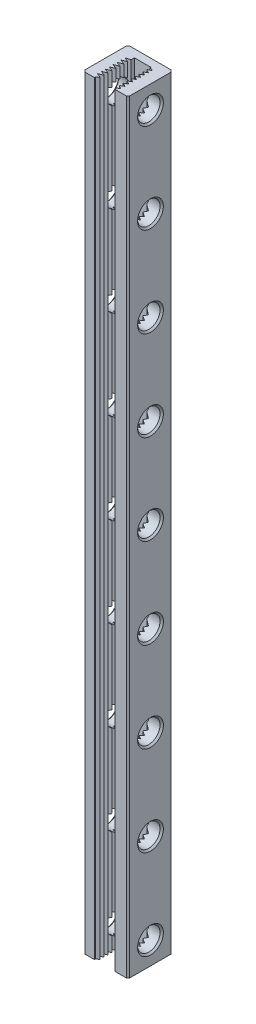
SolidWorks part; units mm, degrees
ref_plane "Front Plane" through (0, 0, 0) normal (0, 0, 1) x (1, 0, 0)
ref_plane "Top Plane" through (0, 0, 0) normal (0, 1, 0) x (1, 0, 0)
ref_plane "Right Plane" through (0, 0, 0) normal (1, 0, 0) x (0, 0, -1)
sketch "Sketch1" plane through (0, 0, 0) normal (0, 1, 0) x (1, 0, 0)
  line L1 (0, 0) -> (8, 0)
  line L2 (0, 0) -> (0, 8)
  line L3 (0, 8) -> (8, 8)
  line L4 (8, 0) -> (8, 8)
  dimension "D1" = 8
  dimension "D2" = 8
extrude "Boss-Extrude1" add sketch "Sketch1" along normal blind 300
sketch "Sketch2" plane through (0, 0, 0) normal (0, -1, 0) x (1, 0, 0)
  line L0 (5.652, 0) -> (2.0084, 0)
  line L1 (2.0084, 0) -> (2.0084, -0.2082)
  line L2 (2.0084, -0.2082) -> (2.54, -0.5151)
  line L3 (2.54, -0.5151) -> (1.6737, -0.8651)
  line L4 (1.6737, -0.8651) -> (2.54, -1.2151)
  line L5 (2.54, -1.2151) -> (1.6737, -1.5727)
  line L6 (1.6737, -1.5727) -> (2.54, -1.9151)
  line L7 (2.54, -1.9151) -> (1.6737, -2.2651)
  line L8 (1.6737, -2.2651) -> (2.54, -2.6151)
  line L9 (2.54, -2.6151) -> (1.6737, -2.9651)
  line L10 (1.6737, -2.9651) -> (2.54, -3.3151)
  line L11 (2.54, -3.3151) -> (1.6737, -3.6651)
  line L12 (1.6737, -3.6651) -> (2.54, -4.0151)
  line L13 (2.54, -4.0151) -> (1.6737, -4.3651)
  line L14 (1.6737, -4.3651) -> (2.54, -4.7151)
  line L15 (2.54, -4.7151) -> (1.6737, -5.0651)
  line L16 (1.6737, -5.0651) -> (2.54, -5.4151)
  line L17 (2.54, -5.4151) -> (1.6737, -5.7651)
  line L18 (1.6737, -5.7651) -> (2.54, -6.0264)
  line L19 (2.54, -6.0264) -> (2.54, -6.6)
  line L20 (2.54, -6.6) -> (5.46, -6.6)
  line L21 (5.46, -6.6) -> (5.46, -6.4988)
  line L22 (5.46, -6.4988) -> (6.1067, -6.2375)
  line L23 (6.1067, -6.2375) -> (5.46, -5.8875)
  line L24 (5.46, -5.8875) -> (6.1067, -5.5375)
  line L25 (6.1067, -5.5375) -> (5.46, -5.1875)
  line L26 (5.46, -5.1875) -> (6.1067, -4.8375)
  line L27 (6.1067, -4.8375) -> (5.46, -4.4875)
  line L28 (5.46, -4.4875) -> (6.1067, -4.1375)
  line L29 (6.1067, -4.1375) -> (5.46, -3.7875)
  line L30 (5.46, -3.7875) -> (6.1067, -3.4375)
  line L31 (6.1067, -3.4375) -> (5.46, -3.0875)
  line L32 (5.46, -3.0875) -> (6.1067, -2.7375)
  line L33 (6.1067, -2.7375) -> (5.46, -2.3875)
  line L34 (5.46, -2.3875) -> (6.1067, -2.0375)
  line L35 (6.1067, -2.0375) -> (5.46, -1.6875)
  line L36 (5.46, -1.6875) -> (6.1067, -1.3451)
  line L37 (6.1067, -1.3451) -> (5.46, -0.9875)
  line L38 (5.46, -0.9875) -> (6.1067, -0.6375)
  line L39 (6.1067, -0.6375) -> (5.652, -0.375)
  line L40 (5.652, -0.375) -> (5.652, 0)
  line L41 (0, -8) -> (0, 0) construction
  line L42 (8, -8) -> (0, -8) construction
  line L43 (0, 0) -> (8, 0) construction
  point P41 (0, 0)
  point P42 (0, 0)
  point P43 (0, 0)
  point P44 (0, 0)
  point P51 (0, 0)
  point P52 (0, 0)
  point P53 (4, -6.6)
  dimension "D1" = 2.92
  dimension "D2" = 0.8663
  dimension "D3" = 6.6
  dimension "D4" = 0.6467
  dimension "D5" = 4.433
  dimension "D6" = 4
extrude "Cut-Extrude1" cut sketch "Sketch2" against normal through all contours L0 L1 L2 L3 L4 L5 L6 L7 L8 L9 L10 L11 L12 L13 L14 L15 L16 L17 L18 L19 L20 L21 L22 L23 L24 L25 L26 L27 L28 L29 L30 L31 L32 L33 L34 L35 L36 L37 L38 L39 L40
sketch "Sketch3" plane through (8, 0, 0) normal (1, 0, 0) x (0, 0, -1)
  line L0 (0, 0) -> (8, 0) construction
  line L1 (8, 300) -> (8, 0) construction
  circle A0 centre (4, 4) radius 2
  dimension "D1" = 4
  dimension "D2" = 4
  dimension "D3" = 4
extrude "Cut-Extrude2" cut sketch "Sketch3" against normal through all
chamfer "Chamfer1" distance 0.3 angle 45 2 edges at (0, 4, -6) (8, 4, -6)
chamfer "Chamfer2" distance 0.3 angle 45 4 edges at (0, 150, -8) (0, 150, 0) (8, 150, -8) (8, 150, 0)
pattern_linear "LPattern1" count 19 spacing 16 along (0, 1, 0) of "Cut-Extrude2", "Chamfer1"
sketch "Sketch4" plane through (8, 0, 0) normal (1, 0, 0) x (0, 0, -1)
  line L0 (0.3, 300) -> (7.7, 300) construction
  line L1 (8, 300) -> (0, 300)
  line L2 (8, 300) -> (8, 136)
  line L3 (8, 136) -> (0, 136)
  line L4 (0, 300) -> (0, 136)
  line L5 (0, 0) -> (0, 300) construction
  line L6 (8, 300) -> (8, 0) construction
  line L7 (0.3, 0) -> (7.7, 0) construction
  point P7 (0, 0)
  dimension "D1" = 136
extrude "Cut-Extrude3" cut sketch "Sketch4" against normal through all
